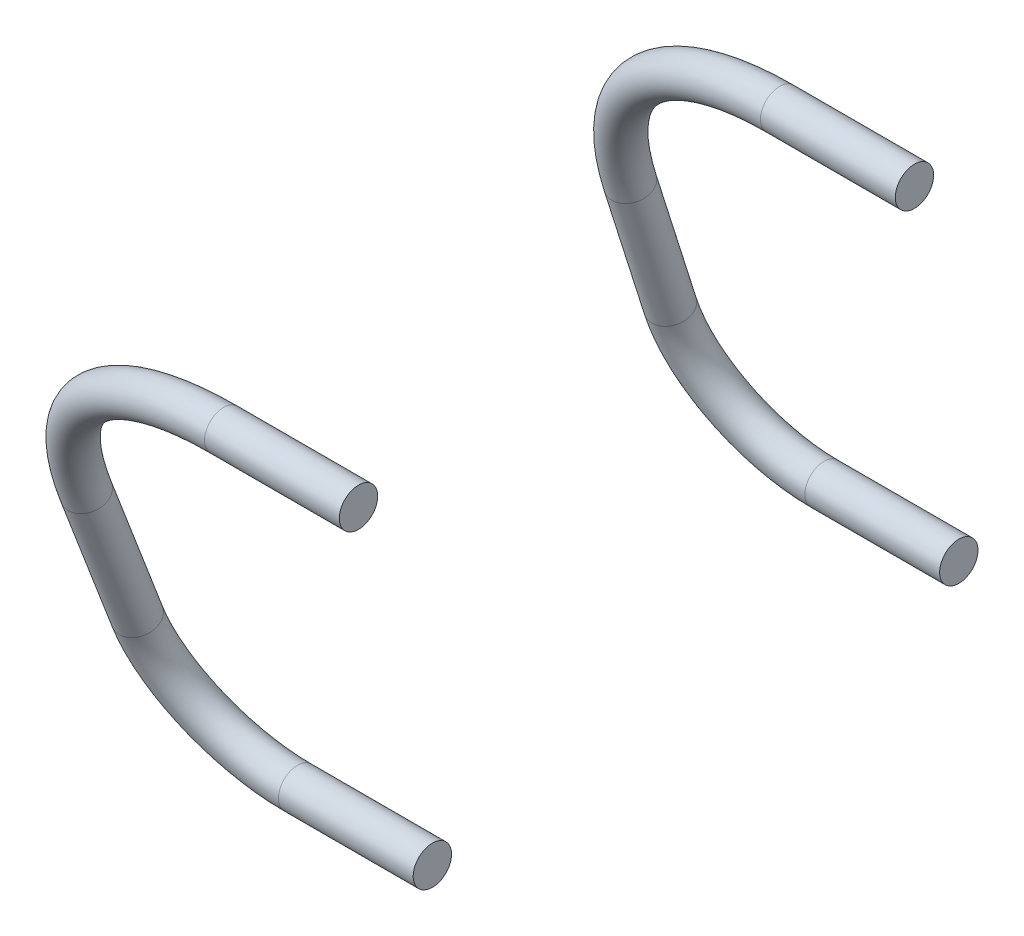
SolidWorks part; units mm, degrees
ref_plane "Front Plane" through (0, 0, 0) normal (0, 0, 1) x (1, 0, 0)
ref_plane "Top Plane" through (0, 0, 0) normal (0, 1, 0) x (1, 0, 0)
ref_plane "Right Plane" through (0, 0, 0) normal (1, 0, 0) x (0, 0, -1)
ref_plane "平面1" through (0, 6.7874, -21.434) normal (0, -0.3019, 0.9533) x (1, 0, 0)
sketch "ｽｹｯﾁ2" plane through (0, 6.7874, -21.434) normal (0, -0.3019, 0.9533) x (1, 0, 0)
  line L0 (-123.0431, 29.5933) -> (-136.7431, 29.5933)
  line L1 (-123.0431, 27.6933) -> (-123.0431, 31.4933) construction
  line L2 (-132.7838, -17.609) -> (-146.4838, -17.609)
  line L3 (-132.7838, -21.359) -> (-132.7838, -13.859) construction
  line L4 (-158.4838, 7.8526) -> (-158.4838, -5.609)
  line L5 (-145.4838, -8.609) -> (-145.4838, -26.609) construction
  line L7 (-135.7431, 38.5933) -> (-135.7431, 20.5933) construction
  arc A0 (-136.7431, 29.5933) -> (-158.4838, 7.8526) centre (-136.7431, 7.8526) ccw
  arc A1 (-146.4838, -17.609) -> (-158.4838, -5.609) centre (-146.4838, -5.609) cw
  dimension "D1" = 13
  dimension "D2" = 1
  dimension "D3" = 1
ref_plane "平面2" through (-123.0431, 0, 0) normal (1, 0, 0) x (0, 0, -1)
sketch "ｽｹｯﾁ3" plane through (-123.0431, 0, 0) normal (1, 0, 0) x (0, 0, -1)
  circle A0 centre (12.5, 35) radius 1.95
  dimension "D1" = 3.9
sweep "ｽｲｰﾌﾟ1" add profiles "ｽｹｯﾁ3" path "ｽｹｯﾁ2"
ref_plane "平面3" through (0, -10.2216, 26.6651) normal (0, -0.3579, 0.9337) x (1, 0, 0)
sketch "ｽｹｯﾁ4" plane through (0, -10.2216, 26.6651) normal (0, -0.3579, 0.9337) x (1, 0, 0)
  line L0 (-123.0431, 48.4303) -> (-136.7431, 48.4303)
  line L1 (-123.0431, 44.6803) -> (-123.0431, 52.1803) construction
  line L2 (-132.7838, 0.2373) -> (-146.4838, 0.2373)
  line L3 (-132.7838, -3.5127) -> (-132.7838, 3.9873) construction
  line L4 (-158.4838, 12.2373) -> (-158.4838, 26.6896)
  line L5 (-135.7431, 57.4303) -> (-135.7431, 39.4303) construction
  line L6 (-145.4838, 9.2373) -> (-145.4838, -8.7627) construction
  arc A0 (-136.7431, 48.4303) -> (-158.4838, 26.6896) centre (-136.7431, 26.6896) ccw
  arc A1 (-146.4838, 0.2373) -> (-158.4838, 12.2373) centre (-146.4838, 12.2373) cw
  point P5 (-158.4838, 4.2195)
  point P12 (-160.7923, 38.8177)
  point P13 (-139.1413, 48.4303)
  point P15 (-137.0715, 48.4303)
  dimension "D1" = 1
  dimension "D2" = 1
  dimension "D3" = 13
sketch "ｽｹｯﾁ5" plane through (-123.0431, 0, 0) normal (1, 0, 0) x (0, 0, -1)
  circle A0 centre (-44, 35) radius 1.95
  dimension "D1" = 3.9
sweep "ｽｲｰﾌﾟ2" add profiles "ｽｹｯﾁ5" path "ｽｹｯﾁ4"
